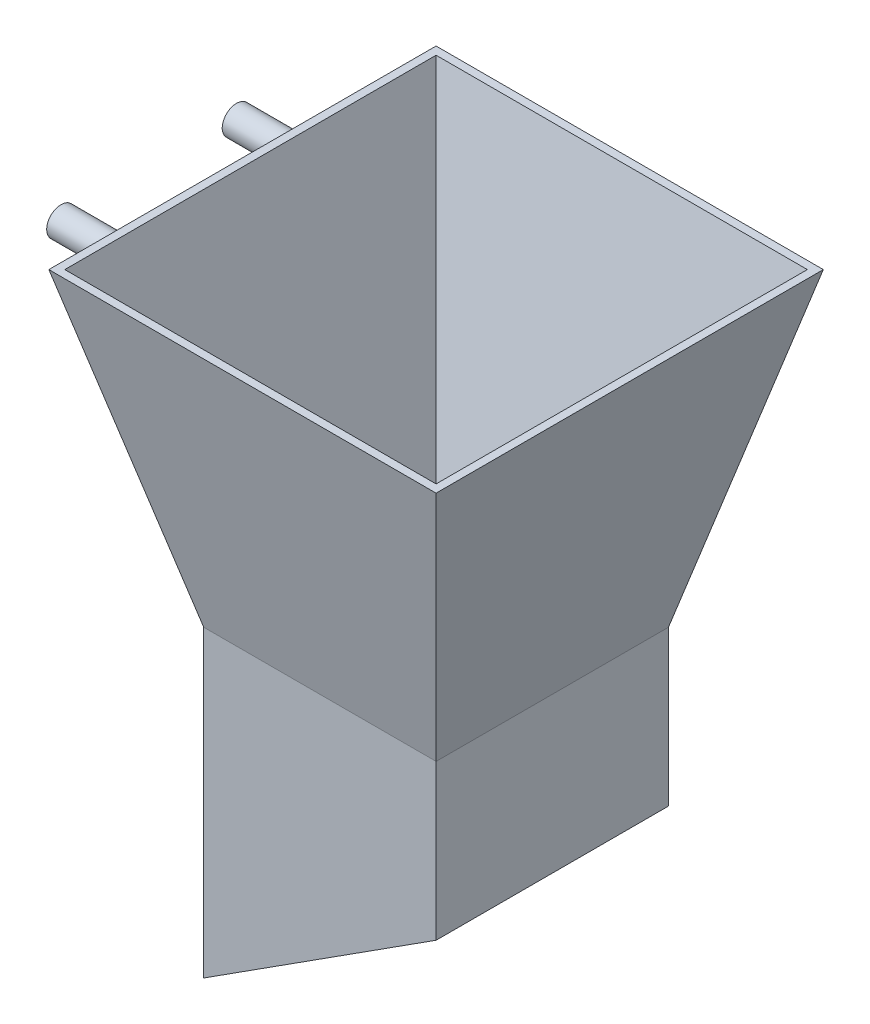
SolidWorks part; units mm, degrees
ref_plane "Alzado" through (0, 0, 0) normal (0, 0, 1) x (1, 0, 0)
ref_plane "Planta" through (0, 0, 0) normal (0, 1, 0) x (1, 0, 0)
ref_plane "Vista lateral" through (0, 0, 0) normal (1, 0, 0) x (0, 0, -1)
sketch "Croquis2" plane through (0, 0, 0) normal (0, 1, 0) x (1, 0, 0)
  line L1 (0, 0) -> (500, 0)
  line L2 (0, 0) -> (0, 500)
  line L3 (0, 500) -> (500, 500)
  line L4 (500, 0) -> (500, 500)
  dimension "D1" = 500
  dimension "D2" = 500
ref_plane "Plano1" through (0, -400, 0) normal (0, 1, 0) x (1, 0, 0)
sketch "Croquis3" plane through (0, -400, 0) normal (0, 1, 0) x (1, 0, 0)
  line L0 (250, 500) -> (250, 0) construction
  line L1 (0, 500) -> (500, 500) construction
  line L2 (0, 0) -> (500, 0) construction
  line L3 (250, 0) -> (500, 250) construction
  line L4 (500, 0) -> (500, 500) construction
  line L5 (500, 250) -> (0, 250) construction
  line L6 (0, 0) -> (0, 500) construction
  line L8 (100, 400) -> (400, 400)
  line L9 (100, 400) -> (100, 100)
  line L10 (100, 100) -> (400, 100)
  line L11 (400, 400) -> (400, 100)
  line L12 (100, 400) -> (400, 100) construction
  line L13 (100, 100) -> (400, 400) construction
  point P12 (250, 250)
  dimension "D1" = 300
  dimension "D2" = 300
loft "Recubrir1" add profiles "Croquis2", "Croquis3"
sketch "Croquis4" plane through (0, -400, 0) normal (0, -1, 0) x (1, 0, 0)
  line L1 (100, -100) -> (400, -100)
  line L2 (100, -100) -> (100, -400)
  line L3 (100, -400) -> (400, -400)
  line L4 (400, -100) -> (400, -400)
  line L5 (100, -100) -> (400, -400) construction
  line L6 (100, -400) -> (400, -100) construction
  point P0 (250, -250)
extrude "Saliente-Extruir1" add sketch "Croquis4" along normal blind 200
sketch "Croquis5" plane through (0, 0, -100) normal (0, 0, 1) x (1, 0, 0)
  line L0 (100, -600) -> (100, -792.1752)
  line L1 (100, -792.1752) -> (400, -600)
  line L2 (400, -600) -> (100, -600) construction
  line L3 (100, -600) -> (400, -600)
extrude "Saliente-Extruir2" add sketch "Croquis5" against normal up to surface (300 mm away) up to face at (287.5, -550, -400)
shell "Vaciado1" thickness 10
ref_plane "Plano2" through (0, 0, 0) normal (1, 0, 0) x (0, 0, -1)
sketch "Croquis6" plane through (0, 0, 0) normal (1, 0, 0) x (0, 0, -1)
  line L0 (250, -50) -> (250, -100) construction
  line L3 (550, -50) -> (-50, -50) construction
  line L4 (-50, -100) -> (550, -100) construction
  line L5 (250, -100) -> (363.3171, -100) construction
  line L6 (363.3171, -100) -> (363.3171, -50) construction
  circle A0 centre (363.3171, -74.7254) radius 18.4816
  circle A1 centre (136.6829, -74.7254) radius 18.4816
  point P9 (363.3171, -74.7254)
extrude "Saliente-Extruir3" add sketch "Croquis6" along normal blind 10 and the other way blind 121 separate body
